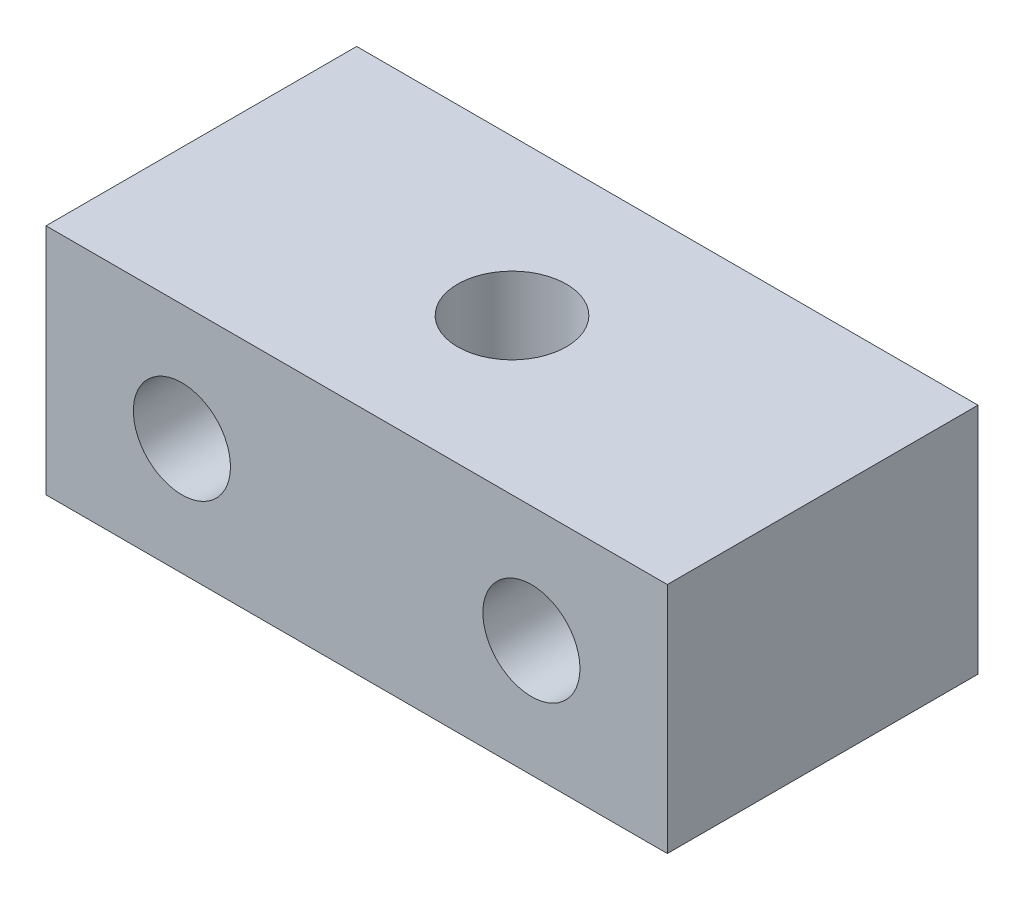
SolidWorks part; units mm, degrees
material "AISI Type A2 Tool Steel"
ref_plane "Front Plane" through (0, 0, 0) normal (0, 0, 1) x (1, 0, 0)
ref_plane "Top Plane" through (0, 0, 0) normal (0, 1, 0) x (1, 0, 0)
ref_plane "Right Plane" through (0, 0, 0) normal (1, 0, 0) x (0, 0, -1)
sketch "Sketch1" plane through (0, 0, 0) normal (0, 0, 1) x (1, 0, 0)
  line L0 (-25.4, 88.9) -> (-25.4, 69.85)
  line L1 (-25.4, 69.85) -> (25.4, 69.85)
  line L2 (25.4, 69.85) -> (25.4, 88.9)
  line L3 (25.4, 88.9) -> (-25.4, 88.9)
  circle A0 centre (-14.2875, 79.375) radius 3.9687
  circle A1 centre (14.2875, 79.375) radius 3.9688
  dimension "D5" = 7.9375
  dimension "D1" = 19.05
  dimension "D2" = 50.8
  dimension "D3" = 88.9
  dimension "D4" = 25.4
  dimension "D6" = 9.525
  dimension "D7" = 9.525
  dimension "D8" = 14.2875
  dimension "D9" = 28.575
extrude "Boss-Extrude2" add sketch "Sketch1" along normal mid plane 25.4
sketch "Sketch2" plane through (0, 0, 0) normal (0, 1, 0) x (1, 0, 0)
  circle A0 centre (0, 0) radius 4.445
extrude "Cut-Extrude1" cut sketch "Sketch2" along normal through all
